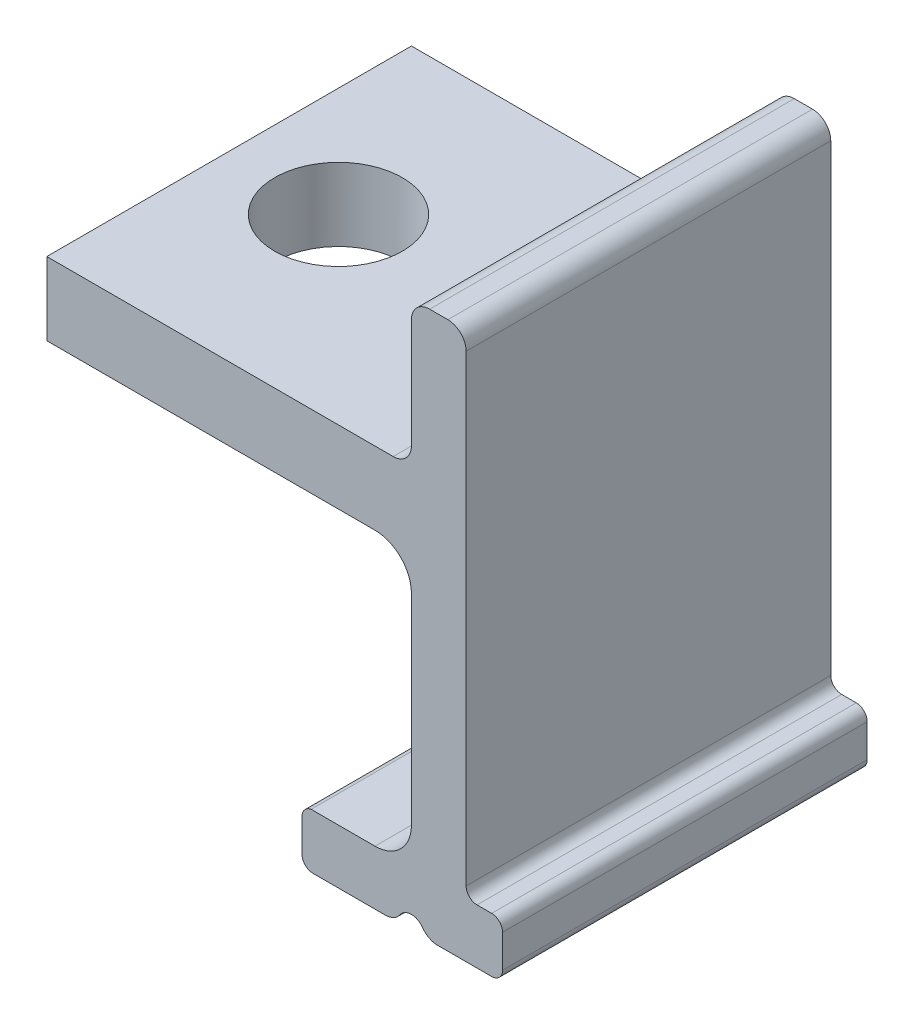
SolidWorks part; units mm, degrees
material "AISI 316"
ref_plane "Front Plane" through (0, 0, 0) normal (0, 0, 1) x (1, 0, 0)
ref_plane "Top Plane" through (0, 0, 0) normal (0, 1, 0) x (1, 0, 0)
ref_plane "Right Plane" through (0, 0, 0) normal (1, 0, 0) x (0, 0, -1)
sketch "Sketch1" plane through (0, 0, 0) normal (0, 0, 1) x (1, 0, 0)
  line L0 (0, 0) -> (9.5, 0)
  line L1 (9.5, 0) -> (9.5, -6.9867) construction
  line L2 (9.5, -6.9867) -> (13.1673, -6.9867) construction
  line L4 (12.2, -11) -> (10.375, -11)
  line L6 (7.3, -2) -> (0, -2)
  line L7 (0, -2) -> (0, 0)
  line L9 (10.375, -11) -> (9.625, -11) construction
  line L10 (9.625, -11) -> (7.3, -11)
  line L12 (11, 4) -> (10.5, 4)
  line L13 (10, 3.5) -> (10, 0.5)
  line L16 (7.5, -2.2) -> (7.5, -9.2084)
  line L17 (7, -9.8) -> (7, -10.7)
  line L18 (12.5, -10.7) -> (12.5, -9.8)
  line L19 (12.2, -9.5) -> (11.8, -9.5)
  line L20 (11.5, -9.2) -> (11.5, 3.5)
  arc A0 (10.375, -11) -> (9.625, -11) centre (10, -11) ccw
  arc A1 (9.625, -11) -> (10.375, -11) centre (10, -11) ccw construction
  arc A3 (11.5, 3.5) -> (11, 4) centre (11, 3.5) ccw
  arc A4 (10.5, 4) -> (10, 3.5) centre (10.5, 3.5) ccw
  arc A5 (10, 0.5) -> (9.5, 0) centre (9.5, 0.5) cw
  arc A7 (7.5, -2.2) -> (7.3, -2) centre (7.3, -2.2) ccw
  arc A8 (7.3, -11) -> (7, -10.7) centre (7.3, -10.7) cw
  arc A11 (12.5, -10.7) -> (12.2, -11) centre (12.2, -10.7) cw
  arc A12 (7, -9.8) -> (7.25, -9.5042) centre (7.3, -9.8) cw
  arc A13 (7.25, -9.5042) -> (7.5, -9.2084) centre (7.2, -9.2084) ccw
  arc A14 (12.5, -9.8) -> (12.2, -9.5) centre (12.2, -9.8) ccw
  arc A15 (11.8, -9.5) -> (11.5, -9.2) centre (11.8, -9.2) cw
  point P18 (12.5, -9.5)
  point P21 (11.5, 4)
  point P24 (10, 4)
  point P29 (9.5, -3.9867)
  point P32 (7.5, -1)
  point P43 (13.1673, -9.9867)
  dimension "D7" = 0.75
  dimension "D10" = 1.5
  dimension "D11" = 0.2
  dimension "D12" = 0.3
  dimension "D14" = 7.5
  dimension "D15" = 0.3
  dimension "D18" = 0.3
  dimension "D16" = 0.3
  dimension "D3" = 0.5
  dimension "D13" = 0.3
  dimension "D2" = 7
  dimension "D4" = 9
  dimension "D5" = 3
  dimension "D6" = 10
  dimension "D8" = 2
  dimension "D9" = 1.5
  dimension "D17" = 0.9
extrude "Boss-Extrude1" add sketch "Sketch1" along normal blind 10
fillet "Fillet1" radius 0.5 2 edges at (9.625, -11, 5) (10.375, -11, 5)
hole_wizard "M3 Clearance Hole1" positions "Sketch2" profile "Sketch3" hole size "M3" standard "ISO" end condition through all
sketch "Sketch2" plane through (0, 0, 0) normal (0, 1, 0) x (1, 0, 0)
  point P0 (3, -5)
sketch "Sketch3" plane through (3, 0, 5) normal (1, 0, 0) x (0, 0, 1)
  line L0 (0, 0) -> (0, 11)
  line L1 (0, 11) -> (1.75, 11)
  line L2 (1.75, 11) -> (1.75, 0)
  line L5 (1.75, 0) -> (0, 0)
  line L11 (0, -6.35) -> (0, 107.95) construction
  dimension "Thru Hole Dia." = 3.5
  dimension "Thru Hole Depth" = 11
sketch "Sketch4" plane through (0, 0, 10) normal (0, 0, 1) x (1, 0, 0)
  line L0 (7.25, -9.5042) -> (9, -9.5042)
  line L1 (10, -8.5042) -> (10, -3)
  line L2 (9, -2) -> (7.5, -2)
  line L3 (7.5, -2.2) -> (7.5, -9.2084) construction
  line L4 (7.5, -2) -> (7.25, -2)
  line L5 (7.25, -2) -> (7.25, -9.5042)
  line L8 (0, -2) -> (7.3, -2) construction
  line L9 (7, -9.8) -> (7, -10.7) construction
  arc A2 (9, -9.5042) -> (10, -8.5042) centre (9, -8.5042) ccw
  arc A3 (10, -3) -> (9, -2) centre (9, -3) ccw
  dimension "D4" = 1
  dimension "D1" = 3
extrude "Cut-Extrude1" cut sketch "Sketch4" against normal blind 10
